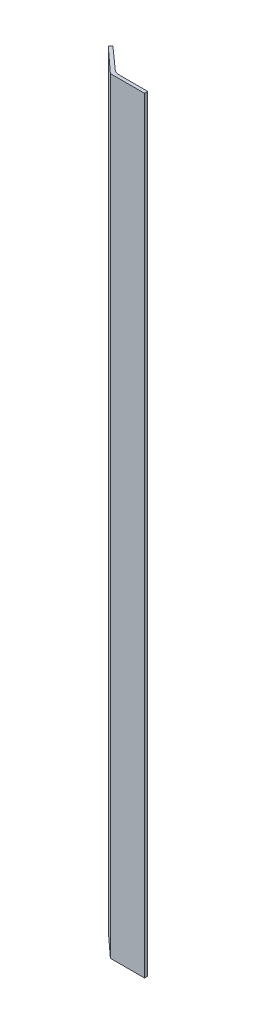
SolidWorks part; units mm, degrees
ref_plane "Спереди" through (0, 0, 0) normal (0, 0, 1) x (1, 0, 0)
ref_plane "Сверху" through (0, 0, 0) normal (0, 1, 0) x (1, 0, 0)
ref_plane "Справа" through (0, 0, 0) normal (1, 0, 0) x (0, 0, -1)
sketch "Эскиз1" plane through (0, 0, 0) normal (0, 1, 0) x (1, 0, 0)
  line L0 (-18.9023, 12.3819) -> (-17.5527, 13.8579)
  line L1 (-0.6446, 0.4869) -> (17.1228, 0.4869)
  line L2 (-17.5527, 13.8579) -> (-3.9712, 1.7541)
  line L3 (-18.9023, 12.3819) -> (-3.7046, -1.5131)
  line L4 (-3.7046, -1.5131) -> (17.1228, -1.5131)
  line L5 (17.1228, -1.5131) -> (17.1228, 0.4869)
  arc A0 (-0.6446, 0.4869) -> (-3.9712, 1.7541) centre (-0.6446, 5.4869) cw
  dimension "D1" = 5
extrude "Вытянуть1" add sketch "Эскиз1" along normal up to surface (468.2137 mm away) from offset 40
